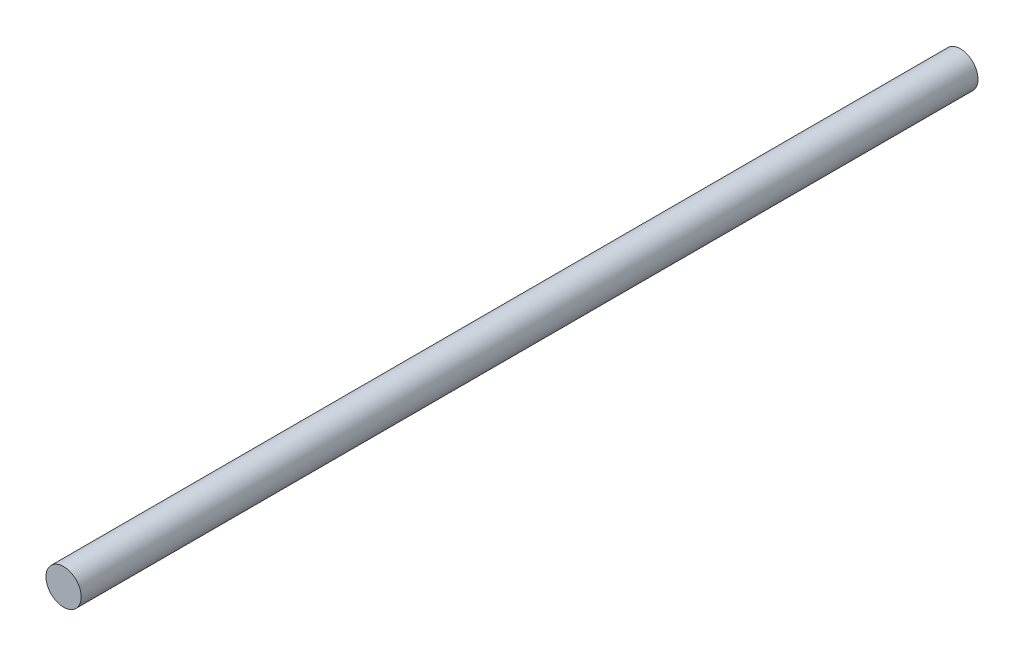
SolidWorks part; units mm, degrees
ref_plane "正面" through (0, 0, 0) normal (0, 0, 1) x (1, 0, 0)
ref_plane "平面" through (0, 0, 0) normal (0, 1, 0) x (1, 0, 0)
ref_plane "右側面" through (0, 0, 0) normal (1, 0, 0) x (0, 0, -1)
sketch "ｽｹｯﾁ1" plane through (0, 0, 0) normal (0, 0, 1) x (1, 0, 0)
  circle A0 centre (0, 0) radius 2.75
  dimension "D1" = 5.5
extrude "ﾎﾞｽ - 押し出し1" add sketch "ｽｹｯﾁ1" along normal blind 140
